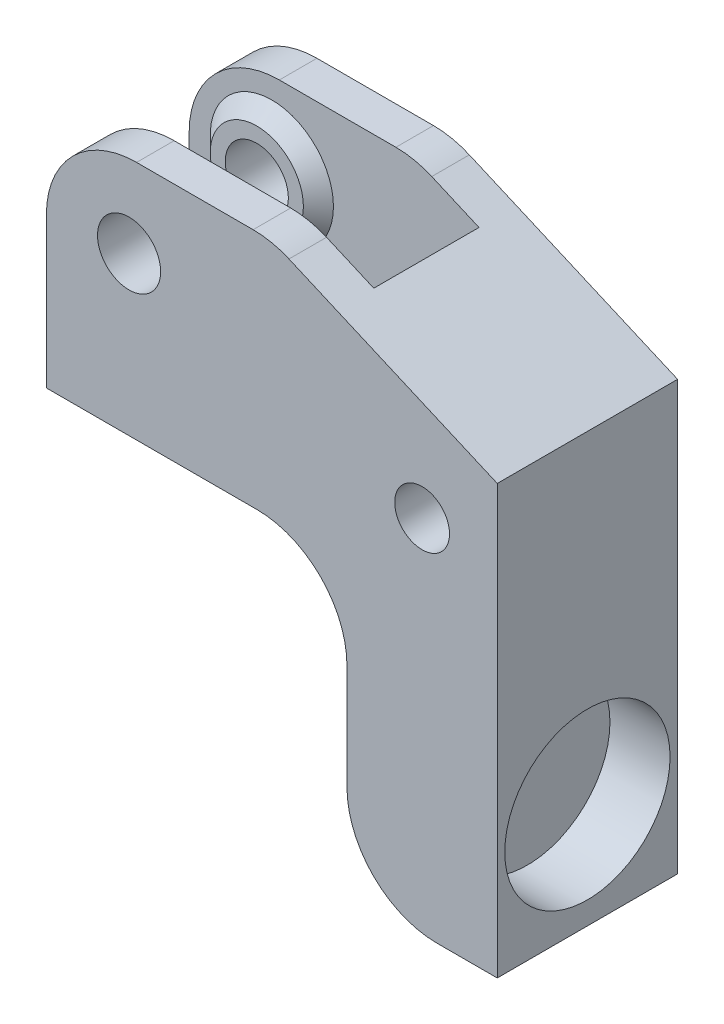
SolidWorks part; units mm, degrees
ref_plane "Front Plane" through (0, 0, 0) normal (0, 0, 1) x (1, 0, 0)
ref_plane "Top Plane" through (0, 0, 0) normal (0, 1, 0) x (1, 0, 0)
ref_plane "Right Plane" through (0, 0, 0) normal (1, 0, 0) x (0, 0, -1)
sketch "Sketch1" plane through (0, 0, 0) normal (0, 0, 1) x (1, 0, 0)
  line L0 (15, 16) -> (30, 9.5)
  line L1 (0, 0) -> (20, 0)
  line L2 (0, 0) -> (0, 16)
  line L3 (0, 16) -> (15, 16)
  line L6 (20, 0) -> (20, -19)
  line L7 (20, -19) -> (30, -19)
  line L8 (30, -19) -> (30, 9.5)
  circle A0 centre (25, 5) radius 1.8222
  circle A1 centre (5.5, 10.5) radius 2.1
  dimension "D6" = 3.6444
  dimension "D9" = 4.2
  dimension "D1" = 16
  dimension "D2" = 4.5
  dimension "D3" = 10
  dimension "D4" = 15
  dimension "D5" = 30
  dimension "D7" = 5
  dimension "D8" = 5
  dimension "D10" = 5.5
  dimension "D11" = 10.5
  dimension "D13" = 35
extrude "Boss-Extrude1" add sketch "Sketch1" along normal blind 12
ref_plane "Plane1" through (0, 0, 6) normal (0, 0, -1) x (-1, 0, 0)
fillet "Fillet1" radius 6 4 edges at (15, 16, 6) (0, 16, 6) (20, -19, 6) (20, 0, 6)
sketch "Sketch2" plane through (0, 0, 6) normal (0, 0, -1) x (-1, 0, 0)
  line L0 (-22, 18.6692) -> (-12, 2)
  line L1 (-12, 2) -> (0, 2)
  line L2 (0, 2) -> (0, 22)
  line L3 (0, 22) -> (-22, 18.6692)
  dimension "D1" = 20
  dimension "D2" = 0
  dimension "D3" = 12
  dimension "D4" = 22
  dimension "D5" = 2
  dimension "D6" = 18.6692
extrude "Cut-Extrude1" cut sketch "Sketch2" against normal blind 3.5 and the other way blind 3.5 contours L3 L0 L1 L2
ref_axis "Axis1" through (5.5, 10.5, 12) along (0, 0, -1)
ref_plane "Plane2" through (5.5, 0, 0) normal (1, 0, 0) x (0, 0, -1)
sketch "Sketch4" plane through (5.5, 0, 0) normal (1, 0, 0) x (0, 0, -1)
  line L0 (-9.5, 12.6) -> (-8.5, 12.6)
  line L1 (-8.5, 12.6) -> (-8.5, 13.6)
  line L2 (-8.5, 13.6) -> (-9.5, 14.6)
  line L3 (-9.5, 14.6) -> (-9.5, 12.6)
  dimension "D1" = 45
  dimension "D2" = 1
  dimension "D3" = 1
revolve "Revolve1" add sketch "Sketch4" angle 360 about axis through (5.5, 10.5, 12) along (0, 0, -1)
mirror "Mirror1" about plane through (0, 0, 6) normal (0, 0, -1) of "Revolve1"
sketch "Sketch5" plane through (30, 0, 0) normal (1, 0, 0) x (0, 0, -1)
  line L0 (-6, -19) -> (-6, -12) construction
  line L1 (-12, -19) -> (0, -19) construction
  circle A0 centre (-6, -12) radius 5.5
  dimension "D1" = 11
  dimension "D2" = 7
extrude "Cut-Extrude2" cut sketch "Sketch5" against normal blind 4
